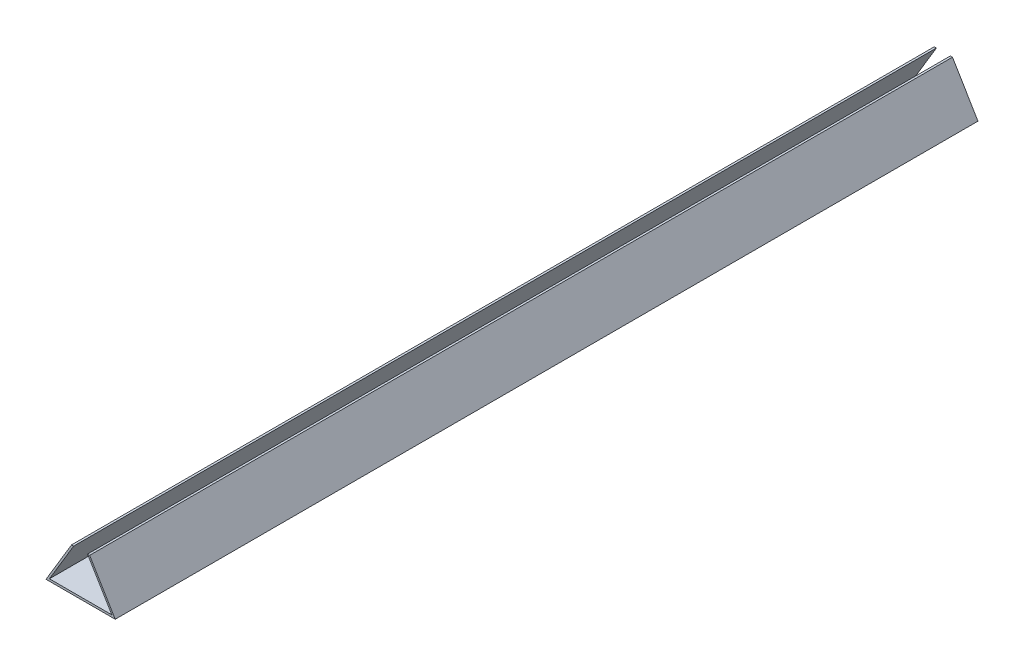
SolidWorks part; units mm, degrees
ref_plane "Alzado" through (0, 0, 0) normal (0, 0, 1) x (1, 0, 0)
ref_plane "Planta" through (0, 0, 0) normal (0, 1, 0) x (1, 0, 0)
ref_plane "Vista lateral" through (0, 0, 0) normal (1, 0, 0) x (0, 0, -1)
sketch "Croquis1" plane through (0, 0, 0) normal (0, 0, 1) x (1, 0, 0)
  line L0 (-32.5, 0) -> (32.5, 0)
  line L1 (32.5, 0) -> (8.5, 40)
  line L2 (-32.5, 0) -> (-8.5, 40)
  line L3 (-6.5, 40) -> (-29.3, 2)
  line L4 (-29.3, 2) -> (29.3, 2)
  line L5 (29.3, 2) -> (6.5, 40)
  line L6 (-6.5, 40) -> (-8.5, 40)
  line L7 (6.5, 40) -> (8.5, 40)
  point P9 (31.3, 2)
  point P10 (-31.3, 2)
  dimension "D1" = 32.5
  dimension "D2" = 32.5
  dimension "D3" = 8.5
  dimension "D4" = 40
  dimension "D5" = 8.5
  dimension "D6" = 40
  dimension "D7" = 2
  dimension "D8" = 2
  dimension "D9" = 2
  dimension "D10" = 2
  dimension "D11" = 2
extrude "Saliente-Extruir1" add sketch "Croquis1" along normal blind 810
